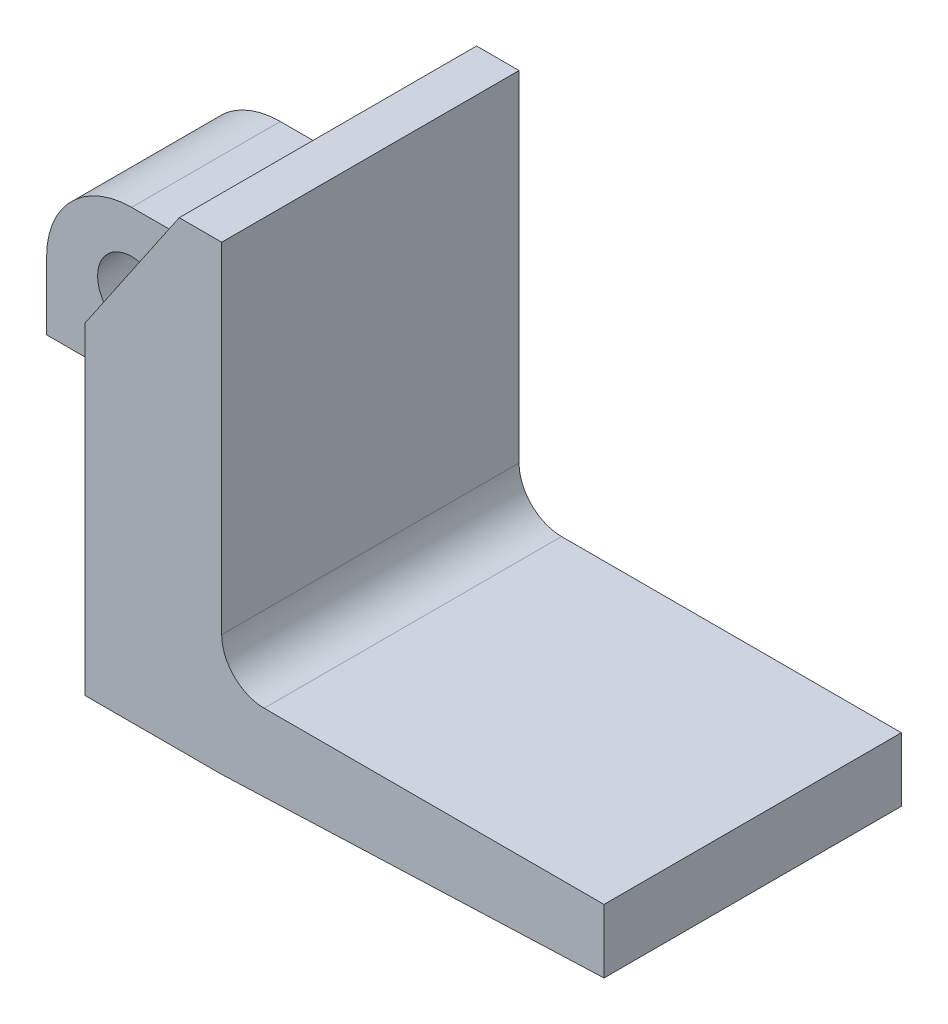
SolidWorks part; units mm, degrees
material "7075-T6 (SN)"
ref_plane "Front Plane" through (0, 0, 0) normal (0, 0, 1) x (1, 0, 0)
ref_plane "Top Plane" through (0, 0, 0) normal (0, 1, 0) x (1, 0, 0)
ref_plane "Right Plane" through (0, 0, 0) normal (1, 0, 0) x (0, 0, -1)
sketch "Sketch1" plane through (0, 0, 0) normal (0, 0, 1) x (1, 0, 0)
  line L0 (0, 0) -> (57.15, 0)
  line L1 (57.15, 0) -> (57.15, -9.525)
  line L2 (-20.4502, 9.8455) -> (-48.3902, 9.8455)
  line L3 (-48.3902, 9.8455) -> (-48.3902, 20.0055)
  line L7 (0, 57.15) -> (0, 0)
  line L8 (-20.4502, 9.8455) -> (-20.4502, -11.7445)
  line L13 (-35.6902, 32.7055) -> (-22.9902, 32.7055)
  line L15 (-22.9902, 32.7055) -> (-6.35, 57.15)
  line L16 (-6.35, 57.15) -> (0, 57.15)
  line L17 (-20.4502, -11.7445) -> (0, -11.7445)
  line L18 (0, -11.7445) -> (57.15, -9.525)
  arc A0 (-35.6902, 32.7055) -> (-48.3902, 20.0055) centre (-35.6902, 20.0055) ccw
  dimension "D5" = 12.7
  dimension "D1" = 57.15
  dimension "D2" = 22.86
  dimension "D3" = 9.525
  dimension "D4" = 35.6902
  dimension "D6" = 9.8455
  dimension "D7" = 25.4
  dimension "D8" = 12.7
  dimension "D9" = 21.59
  dimension "D10" = 10.16
  dimension "D11" = 57.15
  dimension "D12" = 6.35
  dimension "D13" = 27.94
extrude "Boss-Extrude1" add sketch "Sketch1" along normal blind 44.45
fillet "Fillet2" radius 6.35 1 edges at (0, 0, 22.225)
sketch "Sketch3" plane through (0, 0, 44.45) normal (0, 0, 1) x (1, 0, 0)
  line L0 (-48.3902, 9.8455) -> (-20.4502, 9.8455) construction
  line L1 (-48.3902, 20.0055) -> (-48.3902, 9.8455) construction
  line L2 (-22.9902, 32.7055) -> (-35.6902, 32.7055) construction
  line L3 (-48.3902, 9.8455) -> (-20.4502, 9.8455)
  line L4 (-48.3902, 20.0055) -> (-48.3902, 9.8455)
  line L5 (-22.9902, 32.7055) -> (-35.6902, 32.7055)
  line L7 (-20.4502, 9.8455) -> (-20.4502, 36.4368)
  line L8 (-6.35, 57.15) -> (-22.9902, 32.7055) construction
  line L9 (-20.4502, 36.4368) -> (-22.9902, 32.7055)
  arc A0 (-35.6902, 32.7055) -> (-48.3902, 20.0055) centre (-35.6902, 20.0055) ccw construction
  arc A1 (-35.6902, 32.7055) -> (-48.3902, 20.0055) centre (-35.6902, 20.0055) ccw
extrude "Cut-Extrude1" cut sketch "Sketch3" against normal blind 22.225
fillet "Fillet3" radius 2.54 1 edges at (-22.9902, 32.7055, 11.1125)
sketch "Sketch6" plane through (0, 0, 0) normal (0, 0, -1) x (-1, 0, 0)
  line L0 (48.3902, 20.0055) -> (48.3902, 9.8455) construction
  line L1 (48.3902, 9.8455) -> (20.4502, 9.8455) construction
  point P0 (35.6902, 21.2755)
  dimension "D1" = 12.7
  dimension "D2" = 11.43
hole_wizard "3/8 (0.375) Diameter Hole1" positions "Sketch6" profile "Sketch5" hole size "3/8" standard "ANSI Inch" end condition through all
sketch "Sketch5" plane through (-35.6902, 21.2755, 0) normal (1, 0, 0) x (0, 1, 0)
  line L0 (0, 0) -> (0, 44.45)
  line L1 (0, 44.45) -> (5.08, 44.45)
  line L2 (5.08, 44.45) -> (5.08, 0)
  line L5 (5.08, 0) -> (0, 0)
  line L11 (0, -6.35) -> (0, 107.95) construction
  dimension "Thru Hole Dia." = 10.16
  dimension "Thru Hole Depth" = 44.45
chamfer "Chamfer3" [suppressed] distance 0.254 angle 45
chamfer "Chamfer5" [suppressed] distance 0.254 angle 45
